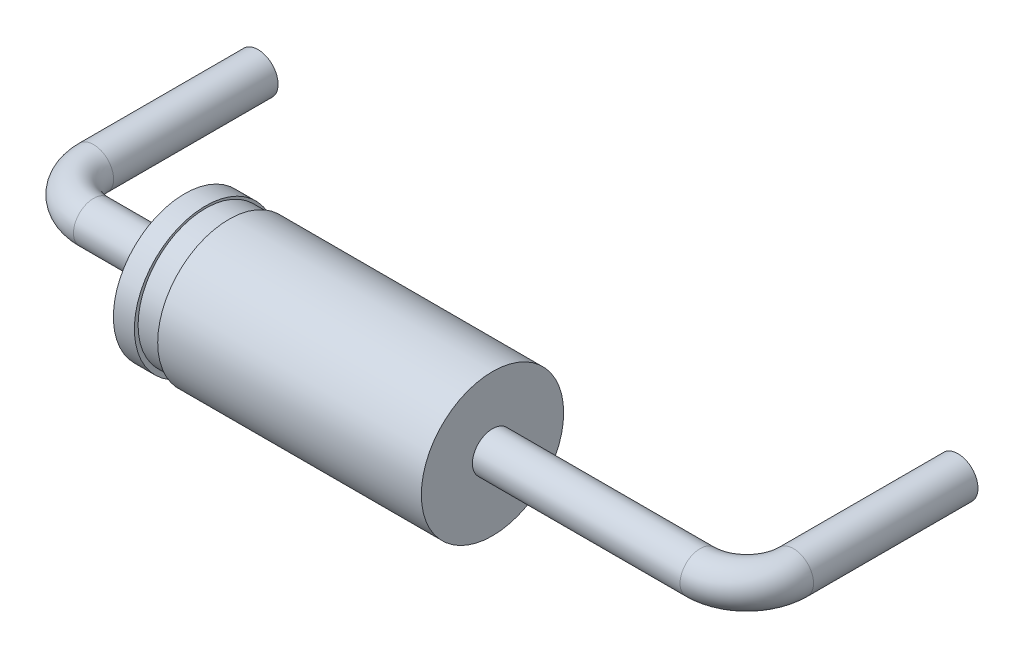
SolidWorks part; units mm, degrees
ref_plane "Front" through (0, 0, 0) normal (0, 0, 1) x (1, 0, 0)
ref_plane "Top" through (0, 0, 0) normal (0, 1, 0) x (1, 0, 0)
ref_plane "Right" through (0, 0, 0) normal (1, 0, 0) x (0, 0, -1)
ref_plane "Плоскость1" through (2.95, 0, 0) normal (1, 0, 0) x (0, 0, -1)
sketch "Эскиз3" plane through (2.95, 0, 0) normal (1, 0, 0) x (0, 0, -1)
  circle A0 centre (-1.525, -0.0336) radius 1.525
  dimension "D2" = 3.05
  dimension "D1" = 1.525
extrude "Вытянуть1" add sketch "Эскиз3" along normal blind 6.6
sketch "Эскиз4" plane through (0, 0, 0) normal (0, 1, 0) x (1, 0, 0)
  line L0 (0, -1.525) -> (10.3423, -1.525) construction
  line L3 (3.4, 0.22) -> (3.9, 0.22)
  line L4 (3.4, 0.22) -> (3.4, -0.08)
  line L5 (3.4, -0.08) -> (3.9, -0.08)
  line L6 (3.9, 0.22) -> (3.9, -0.08)
  dimension "D1" = 1.525
  dimension "D2" = 3.4
  dimension "D3" = 0.5
  dimension "D4" = 0.3
  dimension "D5" = 0.08
revolve "Вырез-Повернуть1" cut sketch "Эскиз4" angle 360 about L0
sketch "Эскиз5" plane through (0, 0, 0) normal (0, 1, 0) x (1, 0, 0)
  line L0 (0, 0) -> (0, -0.525)
  line L1 (3.4, -1.525) -> (2.95, -1.525) construction
  line L2 (1, -1.525) -> (6.8, -1.525)
  line L3 (7.5, 0.7069) -> (7.5, -3.9976) construction
  line L4 (14, -1.525) -> (6.8, -1.525)
  line L5 (15, 0) -> (15, -0.525)
  arc A0 (0, -0.525) -> (1, -1.525) centre (1, -0.525) ccw
  arc A1 (14, -1.525) -> (15, -0.525) centre (14, -0.525) ccw
  point P12 (0, -1.525)
  point P15 (15, -1.525)
  dimension "D2" = 1
  dimension "D3" = 1
  dimension "D1" = 15
sketch "Эскиз6" plane through (0, 0, 0) normal (0, 0, 1) x (1, 0, 0)
  line L0 (7.5, 2.6308) -> (7.5, -2.752) construction
  circle A0 centre (0, 0) radius 0.43
  circle A1 centre (15, 0) radius 0.43
  dimension "D1" = 15
  dimension "D2" = 0.86
sketch "Эскиз7" plane through (0, 0, 0) normal (0, 0, 1) x (1, 0, 0)
  circle A0 centre (0, 0) radius 0.43
  dimension "D1" = 0.86
extrude "Вытянуть2" add sketch "Эскиз6" against normal blind 3
sweep "По траектории1" add profiles "Эскиз7" path "Эскиз5"
